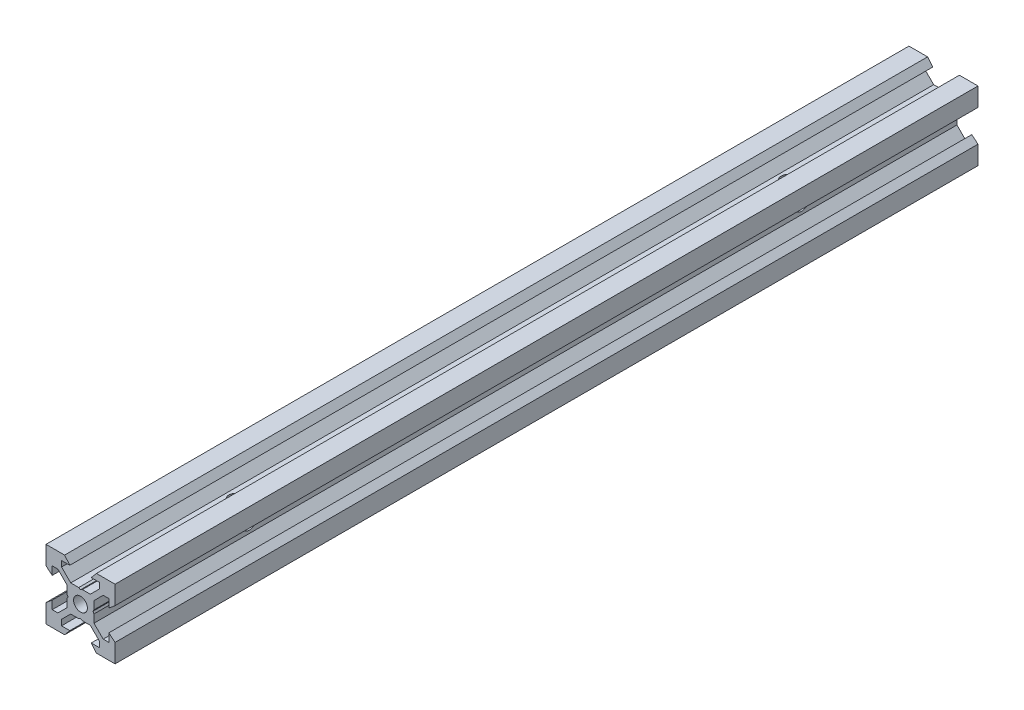
SolidWorks part; units mm, degrees
material "3.3535 (EN-AW 5754)"
ref_plane "Front Plane" through (0, 0, 0) normal (0, 0, 1) x (1, 0, 0)
ref_plane "Top Plane" through (0, 0, 0) normal (0, 1, 0) x (1, 0, 0)
ref_plane "Right Plane" through (0, 0, 0) normal (1, 0, 0) x (0, 0, -1)
sketch "Sketch1" plane through (0, 0, 0) normal (0, 0, 1) x (1, 0, 0)
  line L0 (10, 10) -> (4.6104, 10) construction
  line L1 (10, 10) -> (10, 4.6104) construction
  line L2 (10, -10) -> (10, -4.6104) construction
  line L3 (10, -10) -> (4.6104, -10) construction
  line L4 (10, 10) -> (10, 4.6104)
  line L5 (6.5607, 5.5) -> (8.2, 5.5)
  line L6 (5.5, 8.2) -> (5.5, 6.5607)
  line L7 (10, 10) -> (4.6104, 10)
  line L8 (10, 10) -> (10, 4.6104)
  line L9 (6.5607, 5.5) -> (3.9, 2.8393)
  line L10 (5.5, 6.5607) -> (2.8393, 3.9)
  line L11 (10, 4.6104) -> (8.2, 3.1)
  line L12 (4.6104, 10) -> (3.1, 8.2)
  line L13 (8.2, 3.1) -> (8.2, 5.5)
  line L14 (3.1, 8.2) -> (5.5, 8.2)
  line L15 (-6.5607, 5.5) -> (-8.2, 5.5)
  line L16 (6.5607, -5.5) -> (8.2, -5.5)
  line L17 (3.1, -8.2) -> (5.5, -8.2)
  line L18 (8.2, -3.1) -> (8.2, -5.5)
  line L19 (4.6104, -10) -> (3.1, -8.2)
  line L20 (10, -4.6104) -> (8.2, -3.1)
  line L21 (0.5196, -3.9) -> (0, -3.6)
  line L22 (0.5196, 3.9) -> (0, 3.6)
  line L23 (3.6, 0) -> (3.9, -0.5196)
  line L24 (3.9, 0.5196) -> (3.6, 0)
  line L25 (3.9, 0.5196) -> (3.9, 2.8393)
  line L26 (2.8393, 3.9) -> (0.5196, 3.9)
  line L27 (3.9, -2.8393) -> (3.9, -0.5196)
  line L28 (2.8393, -3.9) -> (0.5196, -3.9)
  line L29 (5.5, -6.5607) -> (2.8393, -3.9)
  line L30 (6.5607, -5.5) -> (3.9, -2.8393)
  line L31 (10, -10) -> (10, -4.6104)
  line L32 (10, -10) -> (4.6104, -10)
  line L33 (5.5, -8.2) -> (5.5, -6.5607)
  line L34 (-6.5607, -5.5) -> (-8.2, -5.5)
  line L35 (10, -10) -> (10, -4.6104)
  line L36 (0, 0) -> (0, 8.2) construction
  line L37 (-10, -10) -> (-4.6104, -10) construction
  line L38 (-10, -10) -> (-10, -4.6104) construction
  line L39 (-10, 10) -> (-10, 4.6104) construction
  line L40 (-10, 10) -> (-4.6104, 10) construction
  line L41 (-10, -10) -> (-10, -4.6104)
  line L43 (-5.5, -8.2) -> (-5.5, -6.5607)
  line L44 (-10, -10) -> (-4.6104, -10)
  line L45 (-10, -10) -> (-10, -4.6104)
  line L46 (-6.5607, -5.5) -> (-3.9, -2.8393)
  line L47 (-5.5, -6.5607) -> (-2.8393, -3.9)
  line L48 (-2.8393, -3.9) -> (-0.5196, -3.9)
  line L49 (-3.9, -2.8393) -> (-3.9, -0.5196)
  line L50 (-2.8393, 3.9) -> (-0.5196, 3.9)
  line L51 (-3.9, 0.5196) -> (-3.9, 2.8393)
  line L52 (-3.9, 0.5196) -> (-3.6, 0)
  line L53 (-3.6, 0) -> (-3.9, -0.5196)
  line L54 (-0.5196, 3.9) -> (0, 3.6)
  line L55 (-0.5196, -3.9) -> (0, -3.6)
  line L56 (-10, -4.6104) -> (-8.2, -3.1)
  line L57 (-4.6104, -10) -> (-3.1, -8.2)
  line L58 (-8.2, -3.1) -> (-8.2, -5.5)
  line L59 (-3.1, -8.2) -> (-5.5, -8.2)
  line L60 (-10, -10) -> (10, -10) construction
  line L61 (-10, -10) -> (-10, 10) construction
  line L62 (-3.1, 8.2) -> (-5.5, 8.2)
  line L63 (-8.2, 3.1) -> (-8.2, 5.5)
  line L64 (-4.6104, 10) -> (-3.1, 8.2)
  line L65 (-10, 4.6104) -> (-8.2, 3.1)
  line L66 (-5.5, 6.5607) -> (-2.8393, 3.9)
  line L67 (-6.5607, 5.5) -> (-3.9, 2.8393)
  line L68 (-10, 10) -> (-10, 4.6104)
  line L69 (-10, 10) -> (-4.6104, 10)
  line L70 (-5.5, 8.2) -> (-5.5, 6.5607)
  line L71 (-10, 10) -> (10, 10) construction
  line L72 (-10, 10) -> (-10, 4.6104)
  line L73 (10, -10) -> (10, 10) construction
  line L74 (-10, -10) -> (10, 10) construction
  line L75 (-10, 10) -> (10, -10) construction
  circle A0 centre (0, 0) radius 2
  dimension "D7" = 4
  dimension "D1" = 20
  dimension "D2" = 5.3896
  dimension "D3" = 4.5
  dimension "D4" = 50
  dimension "D5" = 1.8
  dimension "D6" = 1.5104
  dimension "D8" = 5.5
  dimension "D9" = 120
  dimension "D10" = 0.3
  dimension "D11" = 2.3197
  dimension "D12" = 7.8
  dimension "D13" = 7.8
  dimension "D14" = 1.5
  dimension "D15" = 2.6607
extrude "Boss-Extrude1" add sketch "Sketch1" along normal blind 250 contours L70 L62 L64 L69 L68 L65 L63 L15 L67 L51 L52 L53 L49 L46 L34 L58 L56 L41 L44 L57 L59 L43 L47 L48 L55 L21 L28 L29 L33 L17 L19 L32 L31 L20 L18 L16 L30 L27 L23 L24 L25 L9 L5 L13 L11 L4 L7 L12 L14 L6 L10
sketch "Sketch2" plane through (0, -3.9, 0) normal (0, -1, 0) x (-1, 0, 0)
  line L0 (0, -250) -> (0, -205) construction
  line L1 (0, -250) -> (0, 0) construction
  line L2 (0, 0) -> (0, -45) construction
  circle A0 centre (0, -205) radius 2
  circle A1 centre (0, -45) radius 2
  dimension "D2" = 4
  dimension "D4" = 4
  dimension "D1" = 45
  dimension "D3" = 45
extrude "Cut-Extrude1" cut sketch "Sketch2" against normal through all both and the other way through all
sketch "Sketch3" plane through (3.9, 0, 0) normal (1, 0, 0) x (0, 0, -1)
  line L0 (0, 0) -> (-45, 0) construction
  line L1 (-250, 0) -> (0, 0) construction
  line L2 (-250, 0) -> (-205, 0) construction
  circle A0 centre (-45, 0) radius 2
  circle A1 centre (-205, 0) radius 2
  dimension "D2" = 4
  dimension "D4" = 4
  dimension "D1" = 45
  dimension "D3" = 45
extrude "Cut-Extrude2" cut sketch "Sketch3" against normal through all both
